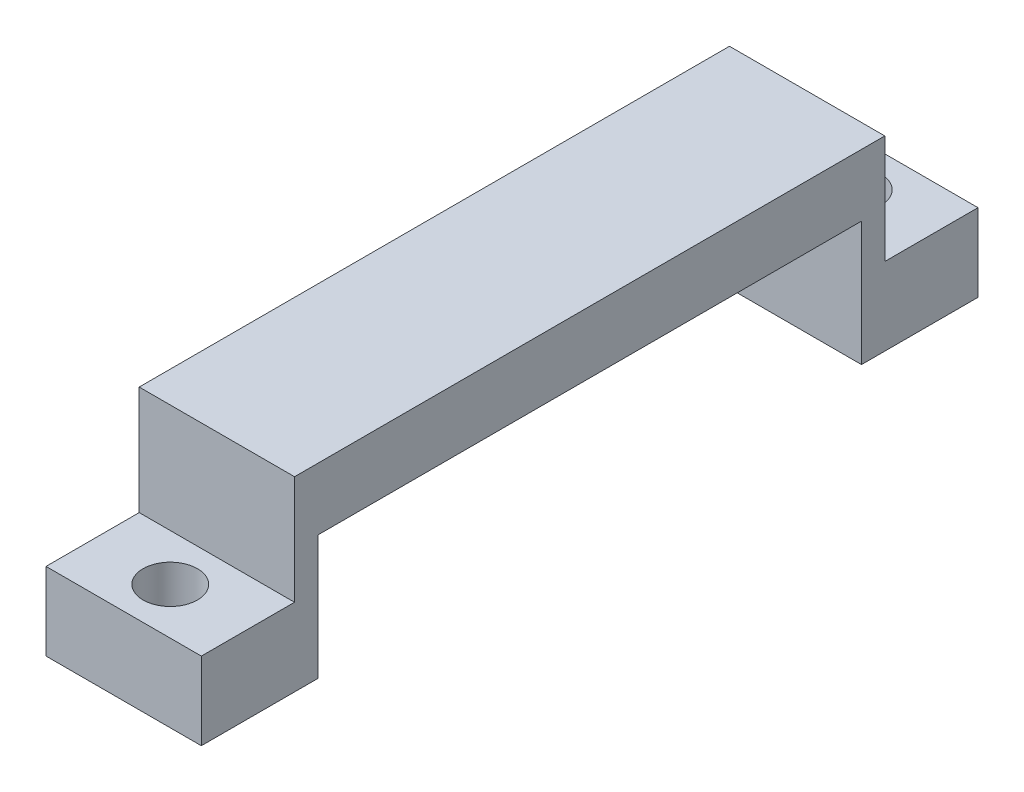
SolidWorks part; units mm, degrees
ref_plane "Alzado" through (0, 0, 0) normal (0, 0, 1) x (1, 0, 0)
ref_plane "Planta" through (0, 0, 0) normal (0, 1, 0) x (1, 0, 0)
ref_plane "Vista lateral" through (0, 0, 0) normal (1, 0, 0) x (0, 0, -1)
sketch "Croquis1" plane through (0, 0, 0) normal (0, 1, 0) x (1, 0, 0)
  line L1 (-20, -25) -> (20, -25)
  line L2 (-20, -25) -> (-20, 25)
  line L3 (-20, 25) -> (20, 25)
  line L4 (20, -25) -> (20, 25)
  line L5 (-20, -25) -> (20, 25) construction
  line L6 (-20, 25) -> (20, -25) construction
  point P0 (0, 0)
  dimension "D1" = 40
  dimension "D2" = 50
extrude "Saliente-Extruir1" add sketch "Croquis1" along normal blind 12
sketch "Croquis2" plane through (20, 0, 0) normal (1, 0, 0) x (0, 0, -1)
  line L0 (22, 0) -> (-22, 0) construction
  line L1 (-17.5, 0) -> (17.5, 0)
  line L2 (-17.5, 0) -> (-17.5, 8)
  line L3 (-17.5, 8) -> (17.5, 8)
  line L4 (17.5, 0) -> (17.5, 8)
  line L5 (0, 6.6) -> (0, -6.6) construction
  line L6 (-25, 12) -> (25, 12) construction
  dimension "D1" = 35
  dimension "D2" = 17.5
  dimension "D3" = 4
extrude "Cortar-Extruir1" cut sketch "Croquis2" against normal blind 65 contours L3 L4 L1 L2
sketch "Croquis3" plane through (0, 12, 0) normal (0, 1, 0) x (1, 0, 0)
  line L0 (-20, -25) -> (20, -25) construction
  line L1 (-20, 25) -> (10, 25)
  line L2 (-20, 25) -> (-20, -25)
  line L3 (-20, -25) -> (10, -25)
  line L4 (10, 25) -> (10, -25)
  dimension "D1" = 30
extrude "Cortar-Extruir2" cut sketch "Croquis3" against normal blind 65
sketch "Croquis4" plane through (0, 12, 0) normal (0, 1, 0) x (1, 0, 0)
  line L0 (20, -25) -> (20, 25) construction
  line L1 (10, 25) -> (20, 25)
  line L2 (10, 25) -> (10, 19)
  line L3 (10, 19) -> (20, 19)
  line L4 (20, 25) -> (20, 19)
  dimension "D1" = 6
extrude "Cortar-Extruir3" cut sketch "Croquis4" against normal blind 7 contours L3 L4 L1 L2
mirror "Simetría1" about plane through (0, 0, 0) normal (0, 0, 1) of "Cortar-Extruir3"
sketch "Croquis5" plane through (0, 5, 0) normal (0, 1, 0) x (1, 0, 0)
  line L0 (20, 25) -> (20, 19) construction
  line L1 (10, 25) -> (20, 25) construction
  circle A0 centre (15, 22) radius 1.75
  dimension "D1" = 3.5
  dimension "D2" = 5
  dimension "D3" = 3
extrude "Cortar-Extruir4" cut sketch "Croquis5" against normal blind 7
mirror "Simetría2" about plane through (0, 0, 0) normal (0, 0, 1) of "Cortar-Extruir4"
